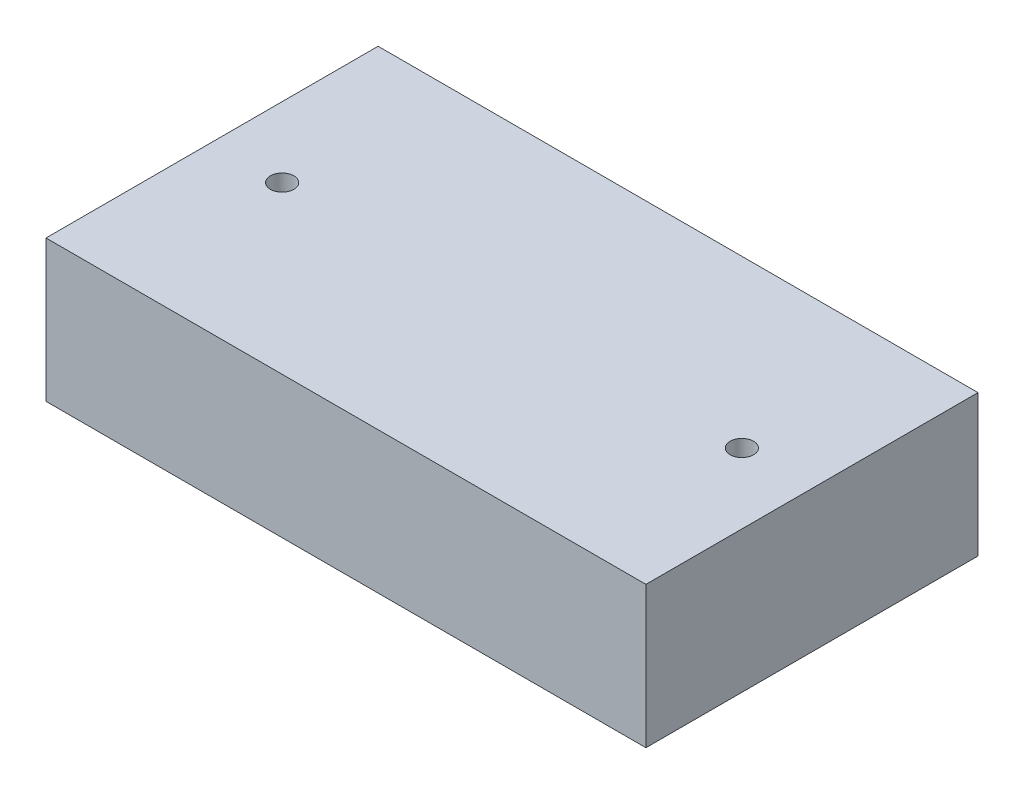
SolidWorks part; units mm, degrees
ref_plane "Спереди" through (0, 0, 0) normal (0, 0, 1) x (1, 0, 0)
ref_plane "Сверху" through (0, 0, 0) normal (0, 1, 0) x (1, 0, 0)
ref_plane "Справа" through (0, 0, 0) normal (1, 0, 0) x (0, 0, -1)
other "Configuration Table"
sketch "Эскиз1" plane through (0, 0, 0) normal (0, 1, 0) x (1, 0, 0)
  line L1 (-38.3, -21.2) -> (38.3, -21.2)
  line L2 (-38.3, -21.2) -> (-38.3, 21.2)
  line L3 (-38.3, 21.2) -> (38.3, 21.2)
  line L4 (38.3, -21.2) -> (38.3, 21.2)
  line L5 (-38.3, -21.2) -> (38.3, 21.2) construction
  line L6 (-38.3, 21.2) -> (38.3, -21.2) construction
  point P0 (0, 0)
  dimension "D1" = 76.6
  dimension "D2" = 42.4
extrude "Бобышка-Вытянуть1" add sketch "Эскиз1" along normal blind 18.07
sketch "Эскиз2" plane through (0, 18.07, 0) normal (0, 1, 0) x (1, 0, 0)
  line L0 (0, 0) -> (58.7, 0) construction
  line L1 (0, 0) -> (0, 38.349) construction
  line L2 (38.3, -21.2) -> (38.3, 21.2) construction
  circle A0 centre (29.35, 0) radius 1.5
  circle A1 centre (-29.35, 0) radius 1.5
  point P6 (30.85, 0)
  dimension "D2" = 3
  dimension "D1" = 7.45
extrude "Вырез-Вытянуть1" cut sketch "Эскиз2" against normal blind 10
sketch "Эскиз3" plane through (0, 0, 0) normal (0, -1, 0) x (1, 0, 0)
  line L0 (0, 0) -> (0, 34.4249) construction
  line L1 (0, 0) -> (65.8176, 0) construction
  circle A0 centre (20, 0) radius 1.5
  circle A1 centre (-20, 0) radius 1.5
  dimension "D1" = 3
  dimension "D2" = 20
extrude "Вырез-Вытянуть2" cut sketch "Эскиз3" against normal blind 10
